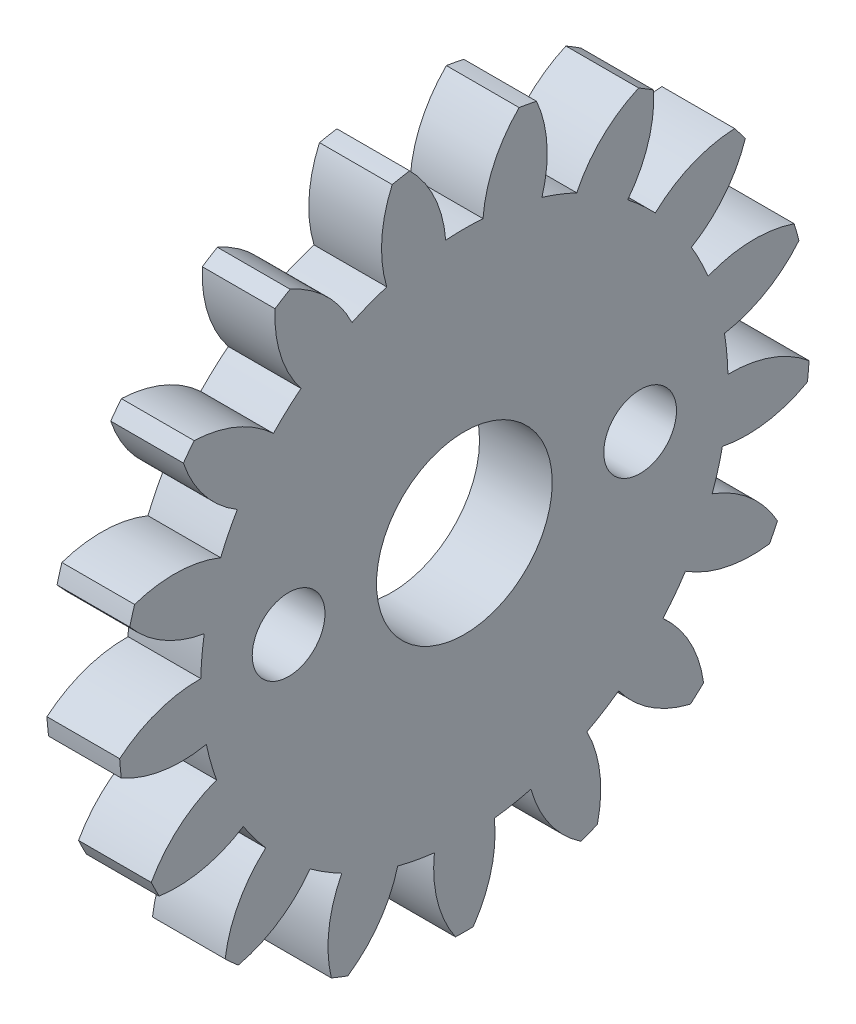
SolidWorks part; units mm, degrees
ref_plane "Plane1" through (0, 0, 0) normal (0, 0, 1) x (1, 0, 0)
ref_plane "Plane2" through (0, 0, 0) normal (0, 1, 0) x (1, 0, 0)
ref_plane "Plane3" through (0, 0, 0) normal (1, 0, 0) x (0, 0, -1)
sketch "HoldingSke" plane through (0, 0, 0) normal (0, 1, 0) x (1, 0, 0)
  line L0 (0, 0) -> (0.6375, -0.1949)
  line L1 (-15, 0) -> (100, 0) construction
  line L2 (0, 0) -> (-2.1039, 2.3779)
  line L3 (0, 0) -> (-11.863, 4.5341)
  line L4 (0, 0) -> (8.2586, 2.5249)
  line L5 (0, 0) -> (-46.8476, -17.4728)
  line L6 (0, 0) -> (-2.4869, -1.6779)
  line L7 (-2.1039, 2.3779) -> (8.6586, 51.2059)
  line L8 (-76.2, 54.61) -> (-75.3, 54.61)
  line L9 (-71.009, 38.7566) -> (-53.1078, 45.2721)
  line L10 (-76.2, 71.12) -> (104.1128, 71.12)
  line L11 (0, 0) -> (-3, 0)
  line L12 (-76.2, 101.6) -> (-76.147, 101.6)
  line L13 (24.9733, 27.94) -> (52.9518, 28.4284)
  line L14 (24.9733, 27.94) -> (24.9743, 27.94)
  line L15 (24.9733, 27.94) -> (100.4006, 29.5858)
  line L16 (-63.627, -1.5) -> (-12.827, -1.5)
  circle A0 centre (0, 0) radius 2.5
  circle A1 centre (0, 0) radius 10.874
  circle A2 centre (0, 0) radius 37.5
  circle A3 centre (0, 0) radius 2.5
  dimension "MHD" = 21.748
  dimension "Hub_dia" = 75
  dimension "Bore" = 5
  dimension "MBD" = 5
  dimension "Num_teeth" = 17
  dimension "Pitch" = 0.6667
  dimension "Overall_len" = 50
  dimension "Show_teeth" = 17
  dimension "Thickness" = 3
  dimension "OAL" = 50.0001
  dimension "T_dim" = 0.9
  dimension "Ap" = 20
  dimension "H" = 19.05
  dimension "Pitch_radius" = 180.3128
  dimension "Width" = 3
  dimension "Backlash" = 0.053
  dimension "Addendum_fac" = 1
  dimension "Dedendum_fac" = 1.25
  dimension "Clearance_fac" = 0.25
  dimension "Dedendum_add" = 0.001
  dimension "Module" = 1.5
sketch "BasProSke" plane through (0, 0, 0) normal (0, 1, 0) x (1, 0, 0)
  line L0 (-10, 0) -> (60, 0) construction
  line L1 (0, 0) -> (0, 14.25)
  line L2 (0, 0) -> (3, 0)
  line L3 (3, 0) -> (3, 14.25)
  line L4 (3, 14.25) -> (0, 14.25)
  dimension "Thickness" = 3
  dimension "Diameter" = 28.5
revolve "Base-Revolve" add sketch "BasProSke" angle 360 about L0
sketch "TooCutSke" plane through (0, 0, 0) normal (1, 0, 0) x (0, 0, -1)
  line L1 (0, 0) -> (0, 107) construction
  line L2 (0, 0) -> (-1.2691, 12.6867) construction
  line L3 (0, 0) -> (-4.6687, 24.9751) construction
  line L4 (-1.2691, 12.6867) -> (-2.3343, 12.4876) construction
  arc A0 (0.7694, 10.8467) -> (-0.7694, 10.8467) centre (0, 0) ccw
  arc A1 (2.2806, 14.0921) -> (-2.2806, 14.0921) centre (0, 0) ccw
  circle A2 centre (0, 0) radius 12.75 construction
  circle A3 centre (0, 0) radius 11.9811 construction
  arc A4 (-0.7694, 10.8467) -> (-2.2806, 14.0921) centre (-5.8542, 10.4535) ccw
  arc A5 (2.2806, 14.0921) -> (0.7694, 10.8467) centre (5.8542, 10.4535) ccw
  dimension "Root_dia" = 21.748
  dimension "Overcut_dia" = 28.5508
  dimension "Pitch_dia" = 25.5
  dimension "Base_dia" = 23.9622
  dimension "Flank_rad" = 5.1
  dimension "Half_ang" = 10.588
  dimension "Half_CT" = 1.0837
extrude "ToothCut" cut sketch "TooCutSke" along normal through all
fillet "Breaks" [suppressed] radius 0.03
fillet "RootFillets" [suppressed] radius 0.376
pattern_circular "TeethCuts" count 17 every 21.176 about axis through (-10, 0, 0) along (1, 0, 0) of "ToothCut", "RootFillets", "Breaks"
sketch "HubNeaOneSke" plane through (0, 0, 0) normal (-1, 0, 0) x (0, 0, 1)
  circle A0 centre (0, 0) radius 10.874
  dimension "Diameter" = 21.748
extrude "HubNearOne" [suppressed] add sketch "HubNeaOneSke" along normal blind 47.0001
sketch "HubNeaBotSke" plane through (0, 0, 0) normal (-1, 0, 0) x (0, 0, 1)
  circle A0 centre (0, 0) radius 10.874
  dimension "Diameter" = 21.748
extrude "HubNearBoth" [suppressed] add sketch "HubNeaBotSke" along normal blind 23.5
ref_plane "FarPln" through (3, 0, 0) normal (1, 0, 0) x (0, 0, -1)
sketch "HubFarSke" plane through (3, 0, 0) normal (1, 0, 0) x (0, 0, -1)
  circle A0 centre (0, 0) radius 10.874
  dimension "Diameter" = 21.748
extrude "HubFar" [suppressed] add sketch "HubFarSke" along normal blind 23.5
sketch "BorSke" plane through (0, 0, 0) normal (1, 0, 0) x (0, 0, -1)
  circle A0 centre (0, 0) radius 2.5
  dimension "Diameter" = 5
extrude "Bore" cut sketch "BorSke" along normal mid plane 100.0001
sketch "KeySke" plane through (0, 0, 0) normal (1, 0, 0) x (0, 0, -1)
  line L0 (-1, 0) -> (-1, 3.4)
  line L1 (-1, 3.4) -> (1, 3.4)
  line L2 (1, 3.4) -> (1, 0)
  line L3 (0, 0) -> (0, 34) construction
  line L4 (-1, 0) -> (1, 0)
  dimension "Offset" = 3.4
  dimension "Width" = 2
extrude "Keyway" [suppressed] cut sketch "KeySke" along normal mid plane 100.0001
pattern_circular "Keyway2" [suppressed] count 2 every 90 about axis through (-10, 0, 0) along (1, 0, 0)
sketch "Croquis1" plane through (3, 0, 0) normal (1, 0, 0) x (0, 0, -1)
  line L0 (0, 0) -> (7.25, 0) construction
  line L1 (0, 50) -> (0, -50) construction
  circle A0 centre (7.25, 0) radius 1.5
  circle A1 centre (0, 0) radius 3.625
  circle A2 centre (-7.25, 0) radius 1.5
  dimension "D2" = 3
  dimension "D3" = 7.25
  dimension "D1" = 7.25
extrude "Cortar-Extruir1" cut sketch "Croquis1" against normal blind 10
sketch "Croquis3" plane through (0, 0, 0) normal (-1, 0, 0) x (0, 0, 1)
  circle A0 centre (0, 0) radius 14.25
  circle A1 centre (0, 0) radius 11
  dimension "D1" = 22
equation "' \"Module@HoldingSke\" = 6.35"
equation "' \"Num_teeth@HoldingSke\" = 12"
equation "' \"Ap@HoldingSke\" =  20"
equation "' \"Ap@HoldingSke\" = 20"
equation "' \"Width@HoldingSke\" = 0.5 * 25.4"
equation "' \"Hub_dia@HoldingSke\"= 1 * 25.4"
equation "' \"Hub_dia@HoldingSke\" = 1 * 25.4"
equation "' \"Overall_len@HoldingSke\" = 1.0 * 25.4"
equation "' \"Bore@HoldingSke\" = 0.75 * 25.4"
equation "' \"T_dim@HoldingSke\" = 0.1 * 25.4"
equation "' \"Width@KeySke\" = 0.25 * 25.4"
equation "' \"Show_teeth@HoldingSke\" = 13"
equation "' \"Backlash@HoldingSke\" = 0.009 * 25.4"
equation "' \"Addendum_fac@HoldingSke\" = 1.0"
equation "' \"Dedendum_fac@HoldingSke\" = 1.25"
equation "' \"Dedendum_add@HoldingSke\" = 0.00005 * 25.4"
equation "' \"Clearance_fac@HoldingSke\" = 0.25"
equation "\"Pitch@HoldingSke\" = 1 / \"Module@HoldingSke\""
equation "\"Overcut_dia@TooCutSke\" = (\"Num_teeth@HoldingSke\" + 2 * \"Addendum_fac@HoldingSke\") / \"Pitch@HoldingSke\" + 0.002 * 25.4"
equation "\"Pitch_dia@TooCutSke\" = \"Num_teeth@HoldingSke\" / \"Pitch@HoldingSke\""
equation "\"Base_dia@TooCutSke\" = \"Num_teeth@HoldingSke\" / \"Pitch@HoldingSke\" * cos((\"Ap@HoldingSke\"  * 3.14159265 / 180))"
equation "\"Root_dia@TooCutSke\" = (\"Num_teeth@HoldingSke\" + 2) / \"Pitch@HoldingSke\" - 2 * (\"Addendum_fac@HoldingSke\" + \"Dedendum_fac@HoldingSke\") / \"Pitch@HoldingSke\" - \"Dedendum_add@HoldingSke\" * 2"
equation "\"Half_ang@TooCutSke\" = 180 / \"Num_teeth@HoldingSke\""
equation "\"Half_CT@TooCutSke\" = \"Num_teeth@HoldingSke\" / \"Pitch@HoldingSke\" * sin((3.14159265 / 2 / \"Num_teeth@HoldingSke\")) / 2 - 7 * \"Backlash@HoldingSke\" / 4"
equation "\"Flank_rad@TooCutSke\" = \"Num_teeth@HoldingSke\" / \"Pitch@HoldingSke\" / 5"
equation "\"Radius@RootFillets\" = \"Clearance_fac@HoldingSke\" / \"Pitch@HoldingSke\" + \"Dedendum_add@HoldingSke\""
equation "\"Break_rad@Breaks\" = 0.02 / \"Pitch@HoldingSke\""
equation "\"Thickness@HoldingSke\" = \"Width@HoldingSke\""
equation "\"OAL@HoldingSke\" = \"Thickness@HoldingSke\""
equation "\"MHD@HoldingSke\" = (\"Num_teeth@HoldingSke\" + 2) / \"Pitch@HoldingSke\" - 2 * (\"Addendum_fac@HoldingSke\" + \"Dedendum_fac@HoldingSke\")  / \"Pitch@HoldingSke\" - \"Dedendum_add@HoldingSke\" * 2"
equation "\"MBD@HoldingSke\" = (\"Num_teeth@HoldingSke\" + 2) / \"Pitch@HoldingSke\" - 2 * (\"Addendum_fac@HoldingSke\" + \"Dedendum_fac@HoldingSke\")  / \"Pitch@HoldingSke\" - \"Dedendum_add@HoldingSke\" * 2 - 0.002 * 25.4"
equation "\"MHD@HoldingSke\" = ((sgn( \"MHD@HoldingSke\" - \"Hub_dia@HoldingSke\" )-1)*( \"MHD@HoldingSke\" - \"Hub_dia@HoldingSke\" ))/-2+ \"Hub_dia@HoldingSke\""
equation "\"MBD@HoldingSke\" = ((sgn( \"MBD@HoldingSke\" - \"Bore@HoldingSke\" )-1)*( \"MBD@HoldingSke\" - \"Bore@HoldingSke\" ))/-2+ \"Bore@HoldingSke\""
equation "\"OAL@HoldingSke\" = ((sgn( \"OAL@HoldingSke\" - \"Overall_len@HoldingSke\" )+1)*( \"OAL@HoldingSke\" - \"Overall_len@HoldingSke\" ))/2 + \"Overall_len@HoldingSke\" + 0.000002 * 25.4"
equation "\"Num_teeth@TeethCuts\" = int( \"Show_teeth@HoldingSke\" ) + 1"
equation "\"Num_teeth@TeethCuts\" = ((sgn( \"Num_teeth@TeethCuts\" - \"Num_teeth@HoldingSke\" )-1)*( \"Num_teeth@TeethCuts\" - \"Num_teeth@HoldingSke\" ))/-2+ \"Num_teeth@HoldingSke\""
equation "\"Num_teeth@TeethCuts\" = ((sgn( \"Num_teeth@TeethCuts\" - 2.0)+1)*( \"Num_teeth@TeethCuts\" - 2.0))/2 +2.0"
equation "\"Angle@TeethCuts\" = 360.0 / \"Num_teeth@HoldingSke\""
equation "\"Diameter@BasProSke\" = (\"Num_teeth@HoldingSke\" + 2 * \"Addendum_fac@HoldingSke\") / \"Pitch@HoldingSke\""
equation "\"Thickness@BasProSke\"  = \"Thickness@HoldingSke\""
equation "' \"Fillet_rad@BasProSke\" =  \"Thickness@HoldingSke\" * 0.05"
equation "' \"Fillet_rad@BasProSke\" = \"Thickness@HoldingSke\" * 0.05"
equation "\"MHD@HoldingSke\" = ((sgn( \"MHD@HoldingSke\" - \"Root_dia@TooCutSke\" )-1)*( \"MHD@HoldingSke\" - \"Root_dia@TooCutSke\" ))/-2+ \"Root_dia@TooCutSke\""
equation "\"Diameter@HubNeaOneSke\" = \"MHD@HoldingSke\""
equation "\"Length@HubNearOne\" = \"OAL@HoldingSke\" - \"Thickness@BasProSke\""
equation "\"Diameter@HubNeaBotSke\" = \"MHD@HoldingSke\""
equation "\"Length@HubNearBoth\" = ( \"OAL@HoldingSke\" - \"Thickness@BasProSke\" ) / 2.0"
equation "\"Thickness@FarPln\" = \"Thickness@BasProSke\""
equation "\"Diameter@HubFarSke\" = \"MHD@HoldingSke\""
equation "\"Length@HubFar\" = ( \"OAL@HoldingSke\" - \"Thickness@BasProSke\" ) / 2.0"
equation "\"Diameter@BorSke\" = \"MBD@HoldingSke\""
equation "\"D1@Bore\" = \"OAL@HoldingSke\" * 2.0"
equation "\"D1@Keyway\" = \"OAL@HoldingSke\" * 2.0"
equation "\"Offset@KeySke\" = \"T_dim@HoldingSke\" + \"MBD@HoldingSke\" / 2.0"
